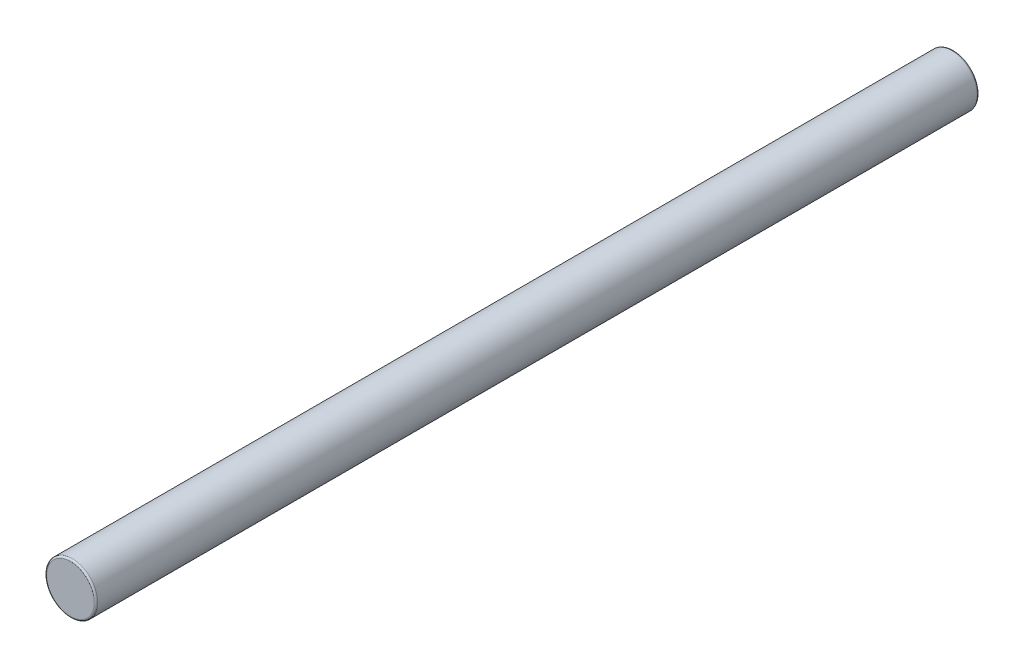
SolidWorks part; units mm, degrees
ref_plane "Plan de face" through (0, 0, 0) normal (0, 0, 1) x (1, 0, 0)
ref_plane "Plan de dessus" through (0, 0, 0) normal (0, 1, 0) x (1, 0, 0)
ref_plane "Plan de droite" through (0, 0, 0) normal (1, 0, 0) x (0, 0, -1)
sketch "Esquisse1" plane through (0, 0, 0) normal (0, 0, 1) x (1, 0, 0)
  circle A0 centre (0, 0) radius 1.5
  dimension "D1" = 3
extrude "Extrusion1" add sketch "Esquisse1" along normal blind 52
fillet "Congé1" radius 0.1 2 edges at (1.5, 0, 52) (1.5, 0, 0)
